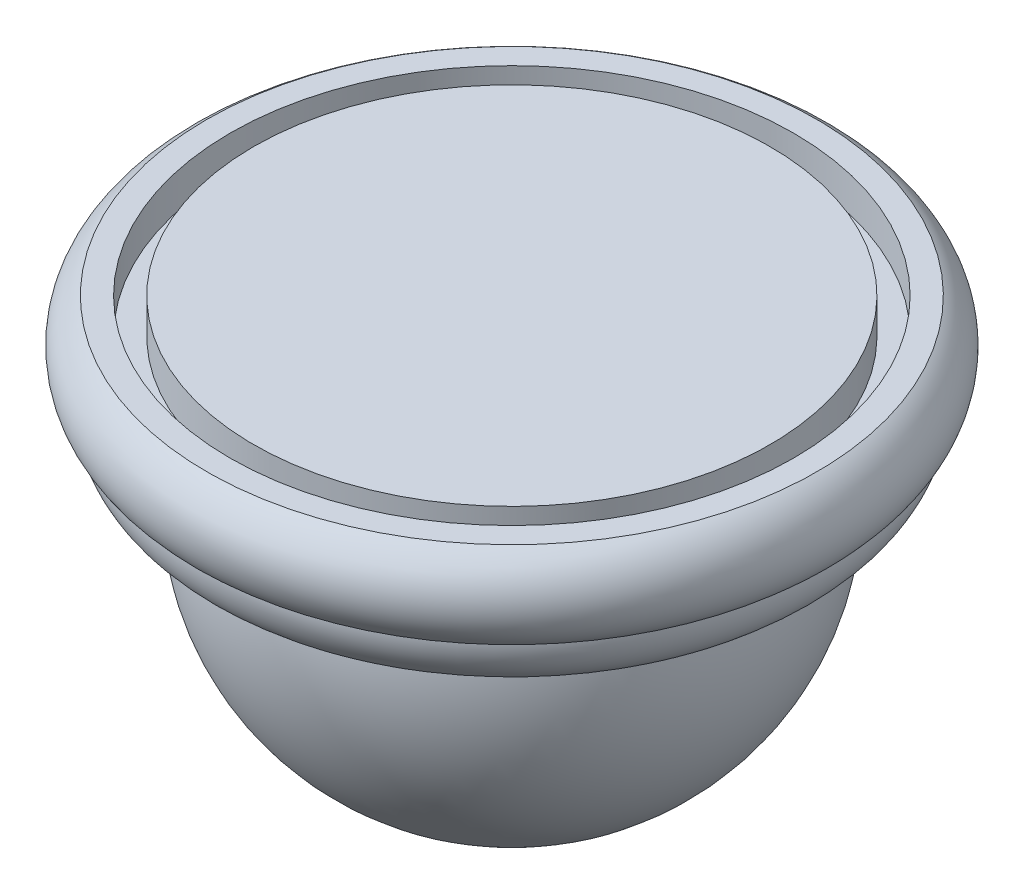
SolidWorks part; units mm, degrees
ref_plane "Front Plane" through (0, 0, 0) normal (0, 0, 1) x (1, 0, 0)
ref_plane "Top Plane" through (0, 0, 0) normal (0, 1, 0) x (1, 0, 0)
ref_plane "Right Plane" through (0, 0, 0) normal (1, 0, 0) x (0, 0, -1)
sketch "Sketch2" plane through (0, 0, 0) normal (0, 0, 1) x (1, 0, 0)
  line L3 (38.1, 7.9375) -> (34.925, 7.9375)
  line L4 (34.925, 7.9375) -> (34.925, 12.7)
  line L5 (34.925, 12.7) -> (0, 12.7)
  line L6 (0, 12.7) -> (0, 0)
  line L7 (0, -44.45) -> (0, 0)
  line L8 (0, 0) -> (0, -44.45) construction
  line L9 (0, -44.45) -> (-22.5294, -44.45) construction
  line L10 (38.1, 7.9375) -> (38.1, 12.7)
  line L11 (38.1, 12.7) -> (41.275, 12.7)
  arc A0 (33.0693, -5.194) -> (42.036, 1.5225) centre (35.2225, 1.2751) ccw
  arc A2 (42.036, 1.5225) -> (41.275, 12.7) centre (37.7777, 6.8472) ccw
  arc A3 (33.0693, -5.194) -> (0, -44.45) centre (0, -10.8932) cw
  point P5 (44.4398, 12.7)
  point P6 (40.7379, 12.7)
  point P10 (42.4236, 12.7)
  point P15 (31.2251, -3.9839)
  point P16 (31.8349, -4.1581)
  point P17 (33.8385, -5.552)
  dimension "D5" = 3.175
  dimension "D7" = 12.7
  dimension "D1" = 38.1
  dimension "D2" = 3.175
  dimension "D3" = 44.45
  dimension "D4" = 4.7625
revolve "Revolve1" add sketch "Sketch2" angle 360 about L6
